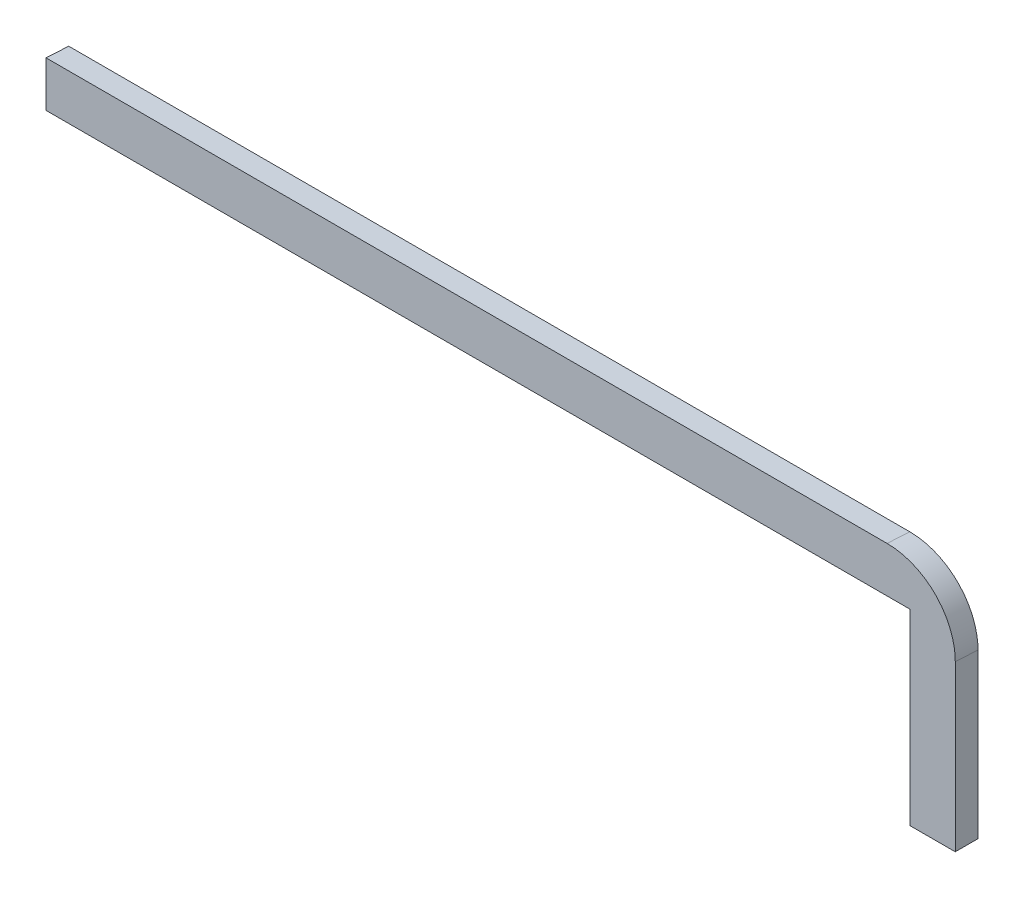
SolidWorks part; units mm, degrees
ref_plane "정면" through (0, 0, 0) normal (0, 0, 1) x (1, 0, 0)
ref_plane "윗면" through (0, 0, 0) normal (0, 1, 0) x (1, 0, 0)
ref_plane "우측면" through (0, 0, 0) normal (1, 0, 0) x (0, 0, -1)
sketch "스케치1" plane through (0, 0, 0) normal (0, 0, 1) x (1, 0, 0)
  line L1 (-40, 50) -> (40, 50)
  line L2 (-40, 50) -> (-40, -50)
  line L3 (-40, -50) -> (40, -50)
  line L4 (40, 50) -> (40, -50)
  line L5 (-40, 50) -> (40, -50) construction
  line L6 (-40, -50) -> (40, 50) construction
  point P0 (0, 0)
  dimension "D1" = 80
  dimension "D2" = 100
extrude "보스-돌출1" add sketch "스케치1" against normal blind 100
sketch "스케치2" plane through (40, 0, 0) normal (1, 0, 0) x (0, 0, -1)
  line L0 (100, -50) -> (100, 50) construction
  line L1 (0, 50) -> (80, 50)
  line L2 (0, 50) -> (0, -35)
  line L3 (0, -35) -> (80, -35)
  line L4 (80, 50) -> (80, -35)
  line L5 (100, -50) -> (0, -50) construction
  dimension "D1" = 20
  dimension "D2" = 15
extrude "컷-돌출1" cut sketch "스케치2" against normal blind 90
sketch "스케치5" plane through (40, 0, 0) normal (1, 0, 0) x (0, 0, -1)
  line L0 (0, -50) -> (0, -35) construction
  line L1 (100, 50) -> (80, 50) construction
  line L2 (96, 50) -> (80, 50)
  line L4 (80, 50) -> (80, -35)
  line L6 (80, -35) -> (0, -35)
  line L8 (80, 50) -> (80, -35)
  line L9 (80, -35) -> (0, -35)
  line L10 (0, -35) -> (0, -50)
  line L11 (0, -50) -> (100, -50)
  line L12 (100, -50) -> (100, 50)
  line L13 (100, 50) -> (80, 50)
  line L15 (80, -35) -> (0, -35)
  line L16 (0, -35) -> (0, -50)
  line L17 (0, -50) -> (100, -50)
  line L18 (100, -50) -> (100, 50)
  line L19 (100, 50) -> (80, 50)
  line L20 (80, 50) -> (80, -35)
  spline S0 degree 3 poles (0, -39.3767) (18.6089, -37.8138) (60.522, -41.4488) (82.6293, -41.815) (94.477, -29.9816) (72.3521, -11.4072) (96, 50) knots 0 0 0 0 0.361872 0.526262 0.755385 1 1 1 1
  dimension "D9" = 9.5231
  dimension "D2" = 22.8534
  dimension "D3" = 11
  dimension "D4" = 8.7853
  dimension "D5" = 36.2853
  dimension "D6" = 13.0435
  dimension "D7" = 22.021
  dimension "D8" = 20
  dimension "D10" = 16
  dimension "D11" = 4.3767
  dimension "D1" = 0
extrude "컷-돌출5" cut sketch "스케치5" against normal through all
shell "쉘2" thickness 2
fillet "필렛1" radius 3 1 edges at (0, 50, -96)
fillet "필렛2" radius 5 1 edges at (0, -39.3767, 0)
fillet "필렛3" radius 3 10 edges at (-40, -47.0329, 0) (-40, -40.6133, -1.3834) (-40, 50, -99.0322) (-40, 49.4694, -96.3609) (40, -47.0329, 0) (40, -40.6133, -1.3834) (40, 50, -99.0322) (40, 49.4694, -96.3609)
ref_plane "평면1" through (40, 47, -98.0645) normal (0, -0.9348, 0.3551) x (-1, 0, 0)
sketch "스케치6" plane through (0, 0, -100) normal (0, 0, -1) x (-1, 0, 0)
  line L0 (-40, -50) -> (-40, 47) construction
  line L1 (-40, -50) -> (-40, 47)
  line L2 (-40, 10) -> (40, 10)
  line L3 (40, 47) -> (40, -50) construction
  line L4 (0, 20.2731) -> (0, 42) construction
  line L5 (-11.9, 11.25) -> (-8.1, 11.25)
  line L6 (-11.9, 11.25) -> (-11.9, 8.75)
  line L7 (-11.9, 8.75) -> (-8.1, 8.75)
  line L8 (-8.1, 11.25) -> (-8.1, 8.75)
  line L9 (-11.9, 11.25) -> (-8.1, 8.75) construction
  line L10 (-11.9, 8.75) -> (-8.1, 11.25) construction
  line L11 (-37, 50) -> (37, 50) construction
  line L12 (11.9, 8.75) -> (8.1, 11.25) construction
  line L13 (11.9, 11.25) -> (8.1, 8.75) construction
  line L14 (8.1, 11.25) -> (8.1, 8.75)
  line L15 (11.9, 8.75) -> (8.1, 8.75)
  line L16 (11.9, 11.25) -> (11.9, 8.75)
  line L17 (11.9, 11.25) -> (8.1, 11.25)
  point P7 (-10, 10)
  point P19 (10, 10)
  dimension "D1" = 3.8
  dimension "D2" = 2.5
  dimension "D3" = 10
  dimension "D4" = 40
extrude "컷-돌출6" cut sketch "스케치6" against normal blind 85 contours L8 L5 L6 L2 | L8 L2 L6 L7 | L16 L2 L14 L15
sketch "스케치8" plane through (0, 50, 0) normal (0, 1, 0) x (1, 0, 0)
  line L0 (-37, 81.3983) -> (-40, 71.8589)
  line L1 (-40, 96) -> (-40, 0) construction
  line L2 (-40, 71.8589) -> (40, 71.8589)
  line L3 (40, 0) -> (40, 96) construction
  line L4 (0, 76.7018) -> (0, 80.7018) construction
  line L5 (-22.5, 71.8589) -> (-17.5, 71.8589)
  line L6 (-22.5, 71.8589) -> (-22.5, 66.8589)
  line L7 (-22.5, 66.8589) -> (-17.5, 66.8589)
  line L8 (-17.5, 71.8589) -> (-17.5, 66.8589)
  line L9 (-22.5, 71.8589) -> (-17.5, 66.8589) construction
  line L10 (-22.5, 66.8589) -> (-17.5, 71.8589) construction
  line L12 (22.5, 66.8589) -> (17.5, 71.8589) construction
  line L13 (22.5, 71.8589) -> (17.5, 66.8589) construction
  line L14 (17.5, 71.8589) -> (17.5, 66.8589)
  line L15 (22.5, 66.8589) -> (17.5, 66.8589)
  line L16 (22.5, 71.8589) -> (22.5, 66.8589)
  line L17 (22.5, 71.8589) -> (17.5, 71.8589)
  point P5 (-20, 69.3589)
  point P14 (0, 71.8589)
  point P20 (20, 69.3589)
  dimension "D1" = 10
  dimension "D2" = 5
  dimension "D3" = 5
  dimension "D4" = 20
extrude "컷-돌출7" cut sketch "스케치8" against normal blind 100 contours L8 L2 L6 L7 | L8 L5 L6 L2 | L16 L17 L14 L2 | L16 L2 L14 L15
sketch "스케치11" plane through (0, 0, -100) normal (0, 0, -1) x (-1, 0, 0)
  line L1 (-22.3234, 3.6269) -> (45.6766, 3.6269) construction
  line L2 (0, 45.5744) -> (0, 67.3013) construction
  line L9 (-37, 50) -> (37, 50) construction
  line L10 (-11, 4.1269) -> (-9, 4.1269)
  line L15 (-11, 4.1269) -> (-11, 3.1269)
  line L16 (-11, 3.1269) -> (-9, 3.1269)
  line L17 (-9, 4.1269) -> (-9, 3.1269)
  line L18 (-11, 4.1269) -> (-9, 3.1269) construction
  line L19 (-11, 3.1269) -> (-9, 4.1269) construction
  line L20 (11, 3.1269) -> (9, 3.1269)
  line L21 (11, 4.1269) -> (11, 3.1269)
  line L22 (11, 4.1269) -> (9, 4.1269)
  line L23 (9, 4.1269) -> (9, 3.1269)
  point P2 (-10, 3.6269)
  dimension "D2" = 2
  dimension "D3" = 1
  dimension "D1" = 46.3731
  dimension "D4" = 10
extrude "컷-돌출8" cut sketch "스케치11" against normal through all
scale "축척1" bodies to scale 119 scale about origin uniform scaling yes scale factor 5
sketch "스케치12" plane through (0, 0, 0) normal (0, 0, 1) x (1, 0, 0)
  line L0 (200, -222.4272) -> (200, 235) construction
  line L1 (-200, 250) -> (200, 250)
  line L2 (-200, 250) -> (-200, -50)
  line L3 (-200, -50) -> (200, -50)
  line L4 (200, 250) -> (200, -50)
  line L5 (-185, 250) -> (185, 250) construction
  line L6 (-200, 235) -> (-200, -222.4272) construction
  line L7 (0, -50) -> (0, -250)
  line L8 (-185, -250) -> (185, -250) construction
  line L9 (0, -250) -> (200, -250)
  line L11 (200, -250) -> (200, -50)
  line L12 (-200, -50) -> (-200, -250)
  line L13 (-200, -250) -> (0, -250)
  line M7 (185, -220.3291) -> (-185, -220.3291)
  line M8 (-185, -220.3291) -> (-185, -250)
  line M9 (-185, -250) -> (185, -250)
  dimension "D1" = 200
extrude "컷-돌출11" cut sketch "스케치12" against normal through all contours L4 L1 L2 L3 | L12 L13 L7 L3 M8 M7 | L7 M7 M8 M9
sketch "스케치15" plane through (0, -250, 0) normal (0, -1, 0) x (1, 0, 0)
  line L0 (200, -200) -> (0, -200)
  line L1 (0, 0) -> (200, 0)
  line L2 (0, 0) -> (0, -500)
  line L3 (0, -500) -> (200, -500)
  line L4 (200, 0) -> (200, -500)
  line L5 (0, -300) -> (200, -300)
  line M4 (185, 0) -> (0, 0)
  line M5 (0, 0) -> (0, -10)
  line M6 (0, -10) -> (190, -10)
  line M7 (190, -10) -> (190, -500)
  line M8 (190, -500) -> (200, -500)
  line M9 (200, -500) -> (200, -15)
  arc M10 (200, -15) -> (185, 0) centre (185, -15) ccw
  dimension "D1" = 200
  dimension "D2" = 100
extrude "컷-돌출13" cut sketch "스케치15" against normal through all contours L2 L0 M6 M7 | L0 M9 M10 M4 M5 M6 M7 | L5 L2 L3 M7 | L5 M7 M8 M9
sketch "스케치16" plane through (200, 0, 0) normal (1, 0, 0) x (0, 0, -1)
  line L0 (300, -250) -> (200, -250) construction
  line L1 (205, -250) -> (300, -250)
  line L2 (205, -250) -> (205, -199.0366)
  line L3 (205, -199.0366) -> (300, -199.0366)
  line L4 (300, -250) -> (300, -199.0366)
  spline S0 degree 3 poles (200, -198.7508) (236.45, -200.8148) (271.0501, -203.2075) (300, -204.9832) knots 0.219193 0.219193 0.219193 0.219193 0.335746 0.335746 0.335746 0.335746 construction
  point P6 (300, -250)
  point P8 (205, -199.0366)
  dimension "D1" = 95
extrude "컷-돌출14" cut sketch "스케치16" against normal through all
